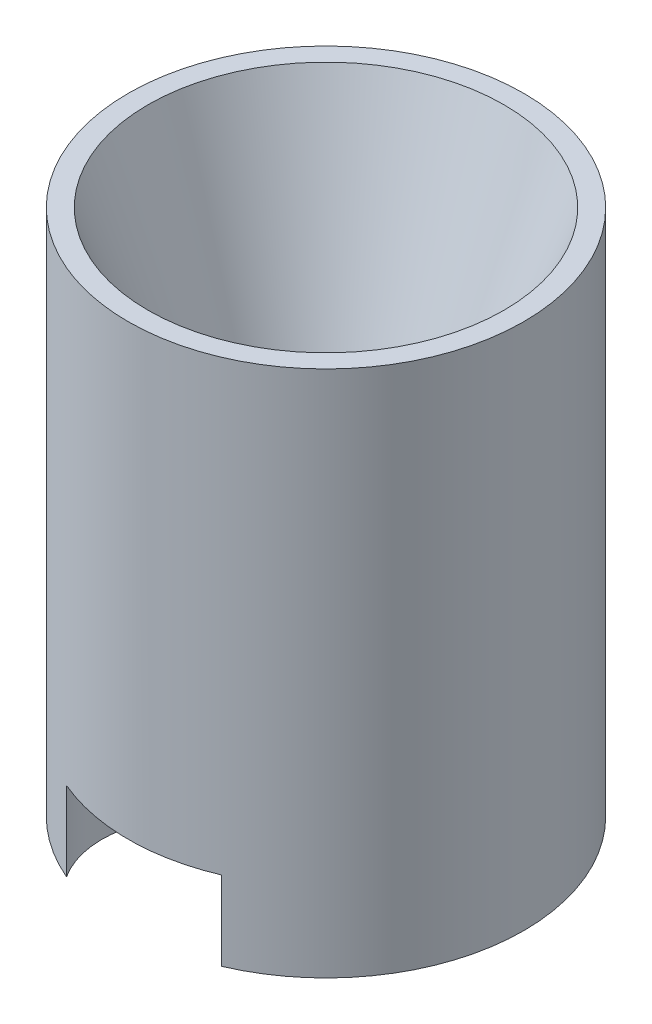
SolidWorks part; units mm, degrees
ref_plane "Front Plane" through (0, 0, 0) normal (0, 0, 1) x (1, 0, 0)
ref_plane "Top Plane" through (0, 0, 0) normal (0, 1, 0) x (1, 0, 0)
ref_plane "Right Plane" through (0, 0, 0) normal (1, 0, 0) x (0, 0, -1)
sketch "Sketch1" plane through (0, 0, 0) normal (0, 1, 0) x (1, 0, 0)
  circle A0 centre (0, 0) radius 7.5
  circle A1 centre (0, 0) radius 0.75
  dimension "D1" = 15
  dimension "D2" = 1.5
extrude "Boss-Extrude1" add sketch "Sketch1" along normal blind 20
chamfer "Chamfer1" distance 6 angle 70 1 edges at (0, 20, 0.75)
sketch "Sketch2" plane through (0, 0, 0) normal (0, -1, 0) x (1, 0, 0)
  line L0 (0, 0) -> (0, 5) construction
  circle A0 centre (0, 5) radius 3.5
  dimension "D2" = 7
  dimension "D1" = 5
extrude "Cut-Extrude1" cut sketch "Sketch2" against normal blind 3
